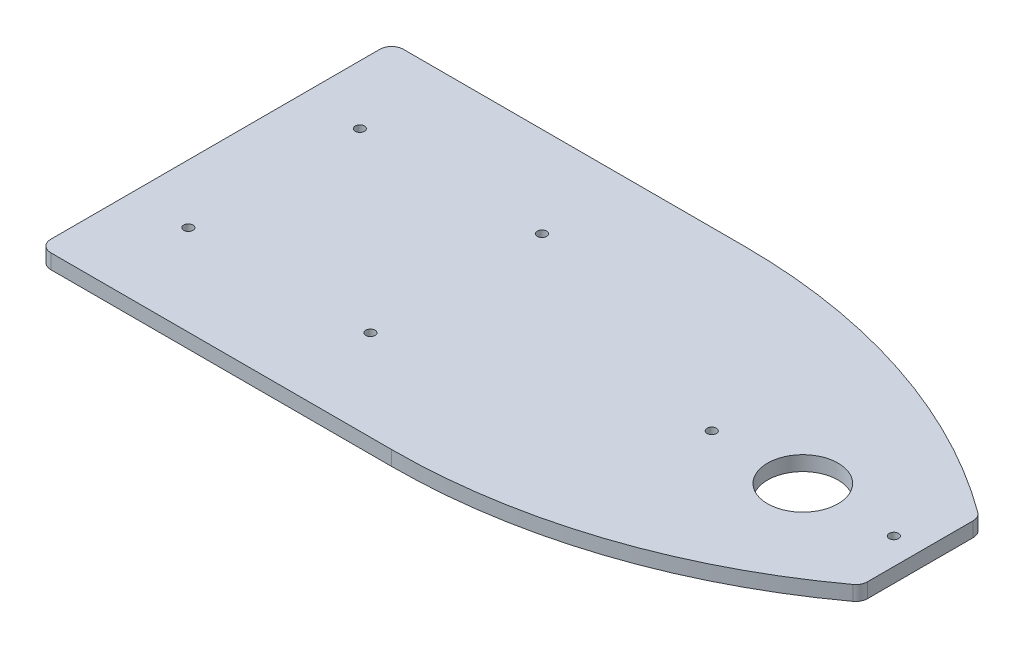
SolidWorks part; units mm, degrees
material "PLA"
ref_plane "Front" through (0, 0, 0) normal (0, 0, 1) x (1, 0, 0)
ref_plane "Top" through (0, 0, 0) normal (0, 1, 0) x (1, 0, 0)
ref_plane "Right" through (0, 0, 0) normal (1, 0, 0) x (0, 0, -1)
sketch "Sketch1" plane through (0, 0, 0) normal (0, 1, 0) x (1, 0, 0)
  line L1 (76.2, -38.1) -> (-76.2, -38.1)
  line L2 (76.2, -38.1) -> (76.2, 38.1)
  line L3 (76.2, 38.1) -> (-76.2, 38.1)
  line L4 (-76.2, -38.1) -> (-76.2, 38.1)
  line L5 (76.2, -38.1) -> (-76.2, 38.1) construction
  line L6 (76.2, 38.1) -> (-76.2, -38.1) construction
  point P0 (0, 0)
  dimension "D1" = 76.2
  dimension "D2" = 152.4
extrude "Boss-Extrude1" add sketch "Sketch1" along normal blind 3.175
sketch "Sketch4" plane through (0, 3.175, 0) normal (0, 1, 0) x (1, 0, 0)
  line L0 (0, 38.1) -> (76.2, 38.1)
  line L1 (76.2, 38.1) -> (-76.2, 38.1) construction
  line L2 (76.2, 38.1) -> (76.2, 12.7)
  line L3 (76.2, -38.1) -> (76.2, 38.1) construction
  line L4 (76.2, -38.1) -> (76.2, -12.7)
  line L5 (76.2, -38.1) -> (0, -38.1)
  line L6 (-76.2, -38.1) -> (76.2, -38.1) construction
  arc A0 (0, -38.1) -> (76.2, -12.7) centre (0, 88.9) ccw
  arc A1 (0, 38.1) -> (76.2, 12.7) centre (0, -88.9) cw
  dimension "D3" = 127
  dimension "D4" = 127
  dimension "D1" = 25.4
  dimension "D2" = 25.4
extrude "Cut-Extrude1" cut sketch "Sketch4" against normal blind 3.175
fillet "Fillet2" radius 2.54 2 edges at (76.2, 1.5875, 12.7) (76.2, 1.5875, -12.7)
fillet "Fillet3" radius 2.54 2 edges at (-76.2, 1.5875, 38.1) (-76.2, 1.5875, -38.1)
sketch "Sketch5" plane through (0, 3.175, 0) normal (0, 1, 0) x (1, 0, 0)
  line L0 (-55, 0) -> (55, 0) construction
  line L1 (76.2, -11.422) -> (76.2, 11.422) construction
  circle A0 centre (50.8, 0) radius 7.62
  dimension "D1" = 15.24
  dimension "D2" = 25.4
extrude "Cut-Extrude2" cut sketch "Sketch5" against normal blind 3.175
sketch "Sketch6" plane through (0, 3.175, 0) normal (0, 1, 0) x (1, 0, 0)
  line L1 (-63.5, 18.542) -> (-63.5, 0)
  line L4 (-24.13, 18.542) -> (-24.13, -18.542)
  line L5 (-1.7463, 0) -> (1.7463, 0) construction
  line L6 (-63.5, 0) -> (-63.5, -18.542)
  circle A5 centre (-63.5, 18.542) radius 1.0033
  circle A6 centre (-24.13, 18.542) radius 1.0033
  circle A7 centre (-24.13, -18.542) radius 1.0033
  circle A8 centre (-63.5, -18.542) radius 1.0033
  point P9 (0, 0)
  dimension "D1" = 18.542
  dimension "D2" = 2.0066
  dimension "D4" = 2.0066
  dimension "D5" = 2.0066
  dimension "D6" = 2.0066
  dimension "D3" = 18.542
sketch "Sketch7" plane through (0, 3.175, 0) normal (0, 1, 0) x (1, 0, 0)
  line L0 (50.8, -7.62) -> (50.8, 7.62)
  line L1 (50.8, 0) -> (70.485, 0)
  line L2 (-1.7463, 0) -> (1.7463, 0) construction
  line L3 (50.8, 0) -> (31.115, 0)
  circle A0 centre (50.8, 0) radius 7.62 construction
  circle A1 centre (70.485, 0) radius 1.0033
  circle A2 centre (31.115, 0) radius 1.0033
  dimension "D3" = 2.0066
  dimension "D4" = 2.0066
  dimension "D1" = 19.685
  dimension "D2" = 19.685
extrude "Cut-Extrude4" cut sketch "Sketch7" against normal through all
extrude "Cut-Extrude5" cut sketch "Sketch6" against normal through all
